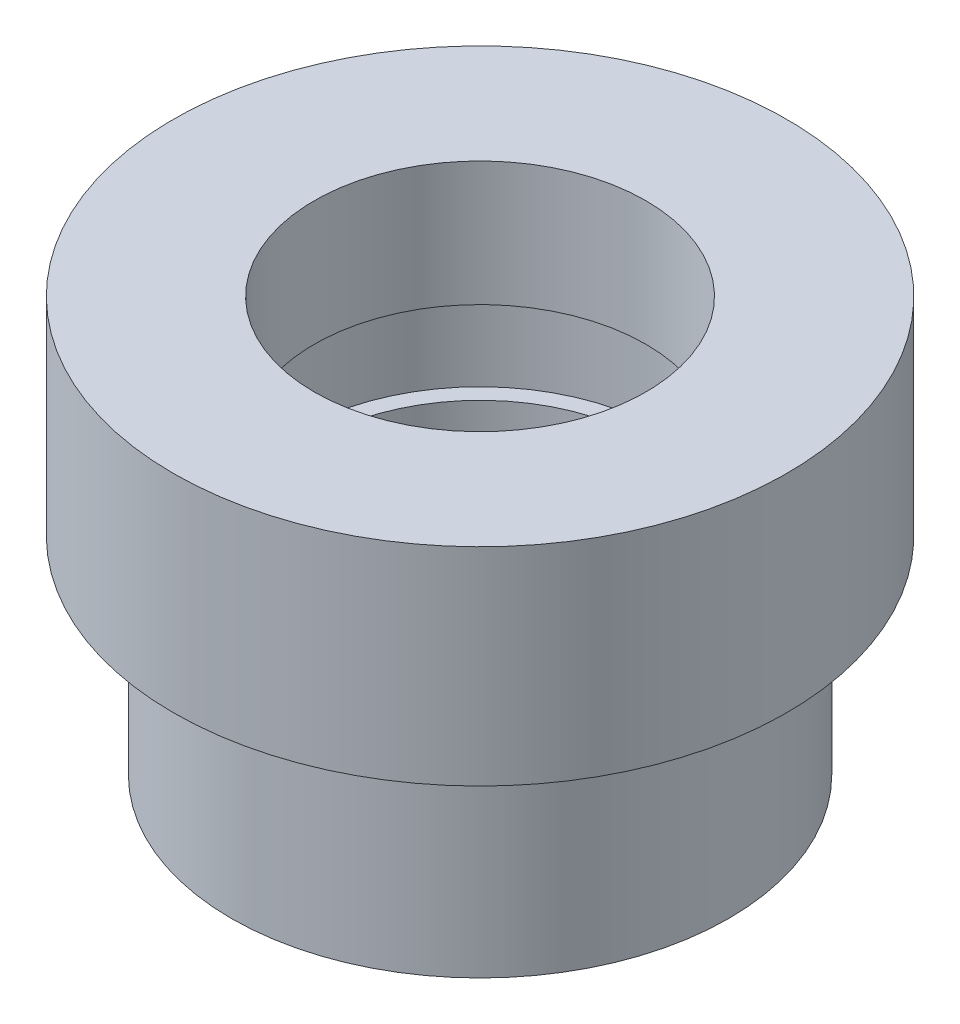
SolidWorks part; units mm, degrees
ref_plane "Alzado" through (0, 0, 0) normal (0, 0, 1) x (1, 0, 0)
ref_plane "Planta" through (0, 0, 0) normal (0, 1, 0) x (1, 0, 0)
ref_plane "Vista lateral" through (0, 0, 0) normal (1, 0, 0) x (0, 0, -1)
sketch "Croquis1" plane through (0, 0, 0) normal (0, 0, 1) x (1, 0, 0)
  line L0 (0, 14.2534) -> (0, -14.5249) construction
  line L1 (-20, 25) -> (-20, 10)
  line L2 (-20, 10) -> (-22, 10)
  line L3 (-22, 10) -> (-22, 0)
  line L4 (-22, 0) -> (-20, 0)
  line L5 (-20, 0) -> (-20, -25)
  line L6 (-20, -25) -> (-30, -25)
  line L7 (-30, -25) -> (-30, 0)
  line L8 (-30, 0) -> (-37, 0)
  line L9 (-37, 0) -> (-37, 25)
  line L10 (-37, 25) -> (-20, 25)
  point P5 (-25, -25)
  dimension "D1" = 20
  dimension "D2" = 17
  dimension "D3" = 25
  dimension "D4" = 50
  dimension "D5" = 10
  dimension "D6" = 2
  dimension "D7" = 10
  dimension "D8" = 7
revolve "Revolución1" add sketch "Croquis1" angle 360 about L0
